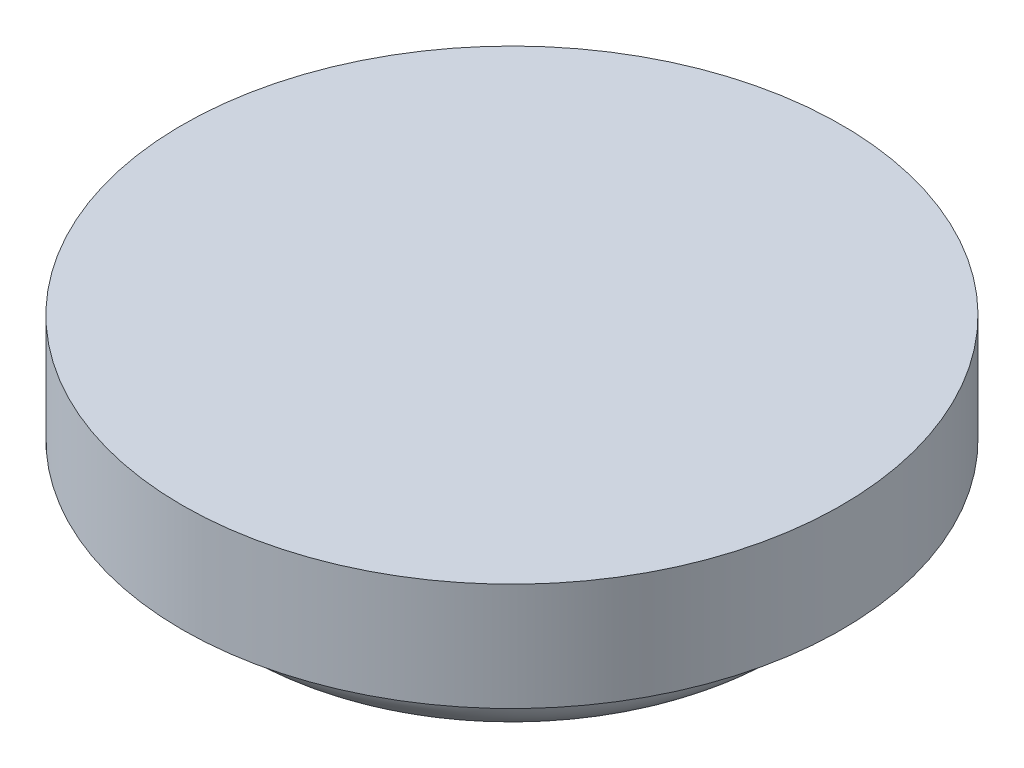
SolidWorks part; units mm, degrees
ref_plane "Спереди" through (0, 0, 0) normal (0, 0, 1) x (1, 0, 0)
ref_plane "Сверху" through (0, 0, 0) normal (0, 1, 0) x (1, 0, 0)
ref_plane "Справа" through (0, 0, 0) normal (1, 0, 0) x (0, 0, -1)
sketch "Эскиз1" plane through (0, 0, 0) normal (0, 1, 0) x (1, 0, 0)
  circle A0 centre (0, 0) radius 6.45
  dimension "D1" = 12.9
extrude "Бобышка-Вытянуть1" add sketch "Эскиз1" along normal blind 1.6
sketch "Эскиз2" plane through (0, 1.6, 0) normal (0, 1, 0) x (1, 0, 0)
  circle A0 centre (0, 0) radius 7.65
  circle A1 centre (0, 0) radius 6.45
  circle A2 centre (0, 0) radius 6.45
  circle M2 centre (0, 0) radius 6.45
  dimension "D1" = 0
  dimension "D2" = 1.2
extrude "Бобышка-Вытянуть2" add sketch "Эскиз2" along normal blind 2.5 contours M2 | A0 M2
fillet "Скругление1" radius 1 1 edges at (0, 0, 6.45)
